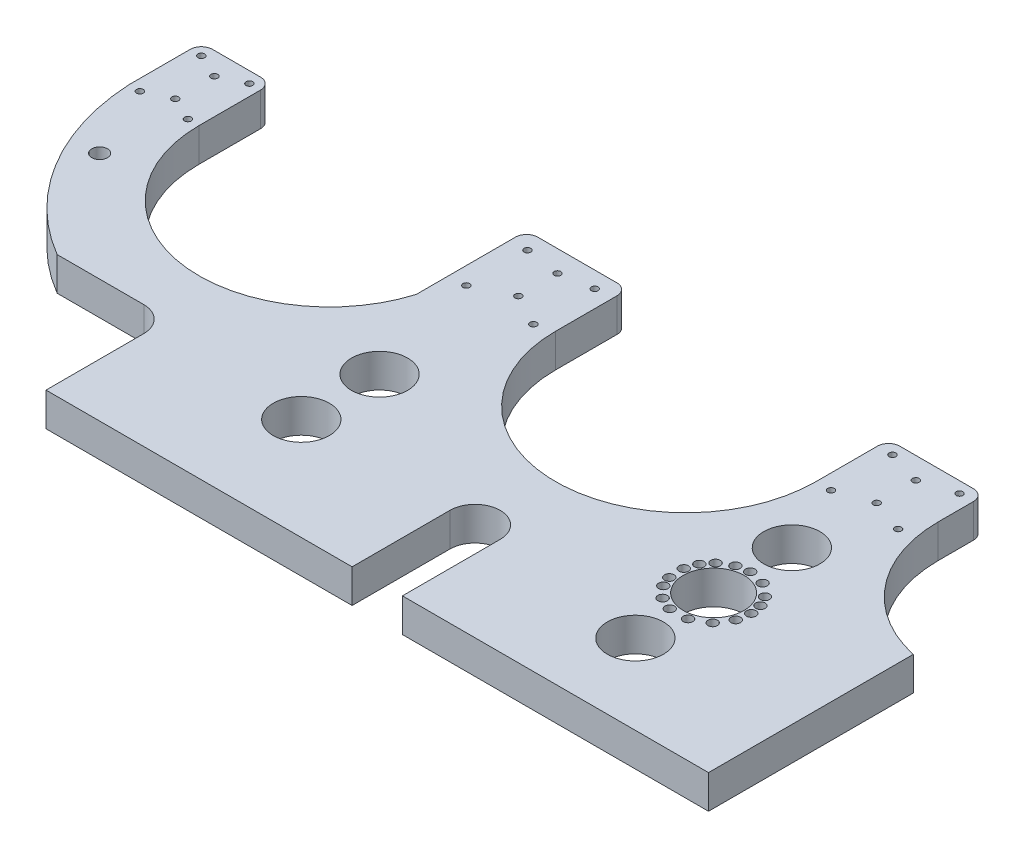
SolidWorks part; units mm, degrees
ref_plane "Front Plane" through (0, 0, 0) normal (0, 0, 1) x (1, 0, 0)
ref_plane "Top Plane" through (0, 0, 0) normal (0, 1, 0) x (1, 0, 0)
ref_plane "Right Plane" through (0, 0, 0) normal (1, 0, 0) x (0, 0, -1)
sketch "Sketch3" plane through (0, 0, 0) normal (0, 1, 0) x (1, 0, 0)
  line L0 (0, 0) -> (273.87, 0)
  line L1 (592.74, 0) -> (592.74, 183.19)
  line L2 (0, 0) -> (-0.0096, 87.5025)
  line L3 (-22.5096, 110) -> (-100.012, 110)
  line L4 (501.24, 296.976) -> (501.24, 328.49)
  line L5 (491.24, 338.49) -> (425.37, 338.49)
  line L6 (415.37, 328.49) -> (415.37, 273.49)
  line L7 (182.37, 273.49) -> (182.37, 328.49)
  line L8 (172.37, 338.49) -> (101.5, 338.49)
  line L9 (91.5, 328.49) -> (91.5, 239.7261)
  line L10 (-136.5, 273.49) -> (-136.5, 328.49)
  line L11 (-146.5, 338.49) -> (-189.5, 338.49)
  line L12 (-199.5, 328.49) -> (-199.5, 273.49)
  line L13 (273.87, 0) -> (273.87, 87.5)
  line L14 (-211.6116, 300.99) -> (-114.2582, 300.99) construction
  line L15 (318.87, 87.5) -> (318.87, 0)
  line L16 (318.87, 0) -> (592.74, 0)
  arc A0 (-100.012, 110) -> (-199.5, 273.49) centre (2.1176, 284.1641) cw
  arc A4 (501.24, 328.49) -> (491.24, 338.49) centre (491.24, 328.49) ccw
  arc A5 (425.37, 338.49) -> (415.37, 328.49) centre (425.37, 328.49) ccw
  arc A6 (182.37, 328.49) -> (172.37, 338.49) centre (172.37, 328.49) ccw
  arc A7 (101.5, 338.49) -> (91.5, 328.49) centre (101.5, 328.49) ccw
  arc A8 (-189.5, 338.49) -> (-199.5, 328.49) centre (-189.5, 328.49) ccw
  arc A9 (-136.5, 328.49) -> (-146.5, 338.49) centre (-146.5, 328.49) ccw
  arc A10 (-0.0096, 87.5025) -> (-22.5096, 110) centre (-22.5096, 87.5) ccw
  arc A11 (501.24, 296.976) -> (592.74, 183.19) centre (617.74, 296.976) ccw
  arc A12 (318.87, 87.5) -> (273.87, 87.5) centre (296.37, 87.5) ccw
  circle A13 centre (-159.5, 207.5) radius 7
  circle A14 centre (-189.5, 328.49) radius 3
  circle A15 centre (-146.5, 328.49) radius 3
  circle A16 centre (-167.8605, 318.49) radius 3
  circle A17 centre (-146.5, 273.49) radius 3
  circle A18 centre (-167.8605, 283.49) radius 3
  circle A19 centre (-189.5, 273.49) radius 3
  circle A20 centre (166.9861, 269.0627) radius 3
  circle A21 centre (166.9861, 323.9251) radius 3
  circle A22 centre (138.4496, 319.1714) radius 3
  circle A23 centre (106.9864, 269.0627) radius 3
  circle A24 centre (106.9864, 323.7368) radius 3
  circle A25 centre (488.8226, 273.49) radius 3
  circle A26 centre (488.8226, 328.49) radius 3
  circle A27 centre (459.0347, 319.1714) radius 3
  circle A28 centre (428.8226, 273.49) radius 3
  circle A29 centre (428.8226, 328.49) radius 3
  circle A30 centre (138.4496, 284.1714) radius 3
  circle A31 centre (459.0347, 284.1714) radius 3
  circle A32 centre (136.93, 161.5) radius 25.1
  circle A33 centre (136.93, 91.5) radius 25.1
  circle A34 centre (455.81, 211.5) radius 25.1
  circle A35 centre (455.81, 71.5) radius 25.1
  circle A36 centre (455.81, 141.5) radius 27.2153
  arc A38 (91.5, 239.7261) -> (-136.5, 273.49) centre (-20, 273.49) cw
  arc A39 (415.37, 273.49) -> (182.37, 273.49) centre (298.87, 273.49) cw
  circle A40 centre (455.81, 141.5) radius 32.75 construction
  circle A41 centre (455.81, 174.25) radius 4.25
  circle A42 centre (470.1294, 170.9537) radius 4.25
  circle A43 centre (481.7438, 161.5) radius 4.25
  circle A44 centre (486.6417, 152.5439) radius 4.25
  circle A45 centre (488.5473, 142.4124) radius 4.25
  circle A46 centre (486.6417, 130.4561) radius 4.25
  circle A47 centre (478.6337, 117.8553) radius 4.25
  circle A48 centre (464.5255, 109.931) radius 4.25
  circle A49 centre (448.4625, 109.5849) radius 4.25
  circle A50 centre (437.0244, 114.6735) radius 4.25
  circle A51 centre (427.8576, 124.4346) radius 4.25
  circle A52 centre (424.0227, 133.6177) radius 4.25
  circle A53 centre (423.5727, 147.0367) radius 4.25
  circle A54 centre (427.1665, 157.3781) radius 4.25
  circle A55 centre (433.5413, 165.5139) radius 4.25
  circle A56 centre (444.5468, 172.2523) radius 4.25
  circle A57 centre (455.81, 141.5) radius 41.8697
  point P34 (182.37, 300.99)
  point P39 (-0.012, 110)
  point P125 (427.8576, 124.4346)
  point P126 (437.0244, 114.6735)
  point P127 (448.4625, 109.5849)
  point P128 (464.5255, 109.931)
  point P129 (486.6417, 130.4561)
  point P130 (488.5473, 142.4124)
  point P131 (486.6417, 152.5439)
  point P132 (481.7438, 161.5)
  point P133 (472.8227, 169.4845)
  point P134 (424.0227, 133.6177)
  point P135 (427.8576, 157.3781)
  point P136 (433.5413, 165.5139)
  point P137 (455.81, 174.25)
  point P138 (470.1294, 170.9537)
  dimension "D4" = 10
  dimension "D10" = 116.5
  dimension "D11" = 116.5
  dimension "D14" = 201.9
  dimension "D17" = 22.5
  dimension "D18" = 273.87
  dimension "D20" = 22.5
  dimension "D21" = 14
  dimension "D25" = 6
  dimension "D26" = 6
  dimension "D27" = 6
  dimension "D35" = 50.2
  dimension "D36" = 50.2
  dimension "D42" = 50.2
  dimension "D43" = 50.2
  dimension "D48" = 54.4305
  dimension "D49" = 65.5
  dimension "D50" = 8.5
  dimension "D1" = 592.74
  dimension "D2" = 183.19
  dimension "D5" = 91.5
  dimension "D6" = 273.87
  dimension "D7" = 90.87
  dimension "D8" = 63
  dimension "D9" = 792.24
  dimension "D12" = 228
  dimension "D13" = 233
  dimension "D15" = 100
  dimension "D16" = 110
  dimension "D19" = 87.5
  dimension "D22" = 97.5
  dimension "D23" = 65.99
  dimension "D24" = 55
  dimension "D28" = 27.5
  dimension "D29" = 35
  dimension "D30" = 60
  dimension "D31" = 35
  dimension "D32" = 60
  dimension "D33" = 35
  dimension "D34" = 40
  dimension "D37" = 91.5
  dimension "D38" = 161.5
  dimension "D39" = 136.94
  dimension "D40" = 45
  dimension "D41" = 136.94
  dimension "D44" = 136.94
  dimension "D45" = 71.5
  dimension "D46" = 70
  dimension "D47" = 70
extrude "Boss-Extrude2" add sketch "Sketch3" along normal blind 30 contours L6 A39 L7 A6 L8 A7 L9 A38 L10 A9 L11 A8 L12 A0 L3 A10 L2 L0 L13 A12 L15 L16 L1 A11 L4 A4 L5 A5 A57 A28 A27 A26 A23 A22 A21 A19 A17 A16 A15 | A57 A36 A41 A42 A43 A44 A45 A46 A47 A48 A49 A50 A51 A52 A53 A54 A55 A56
